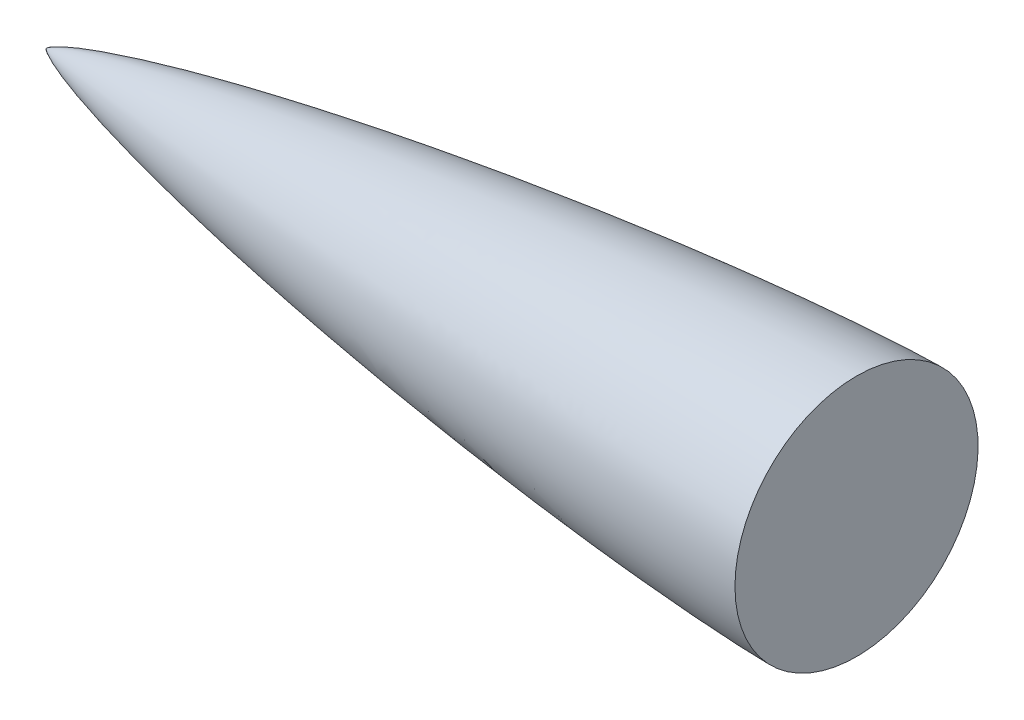
SolidWorks part; units mm, degrees
ref_plane "Front Plane" through (0, 0, 0) normal (0, 0, 1) x (1, 0, 0)
ref_plane "Top Plane" through (0, 0, 0) normal (0, 1, 0) x (1, 0, 0)
ref_plane "Right Plane" through (0, 0, 0) normal (1, 0, 0) x (0, 0, -1)
sketch "Sketch8" plane through (0, 0, 0) normal (0, 0, 1) x (1, 0, 0)
  line L0 (0, 0) -> (20, 0)
  line L1 (20, 0) -> (20, 3)
  spline S0 degree 4 poles (0, 0) (0.0015, 0.0033) (0.0052, 0.0087) (0.0122, 0.0154) (0.0228, 0.0245) (0.0364, 0.0347) (0.0573, 0.0488) (0.0927, 0.07) (0.1548, 0.1029) (0.2682, 0.1555) (0.4717, 0.2373) (0.8108, 0.355) (1.4143, 0.5368) (2.2722, 0.7584) (3.3422, 1.0012) (4.5729, 1.25) (5.8196, 1.4792) (7.3821, 1.7429) (8.9489, 1.9804) (10.5189, 2.1951) (12.0916, 2.388) (13.3514, 2.5294) (14.6126, 2.6574) (15.8751, 2.7712) (17.139, 2.8691) (18.3281, 2.9439) (19.2018, 2.983) (19.7593, 2.9983) (20, 3) knots 0 0 0 0 0 0.000709 0.001299 0.001888 0.002757 0.004048 0.006275 0.010003 0.016613 0.028658 0.049486 0.080709 0.140768 0.203215 0.265661 0.328107 0.390553 0.515445 0.577892 0.640338 0.702784 0.76523 0.827676 0.890122 0.952569 1 1 1 1 1 construction
  spline S1 degree 4 poles (0, 0) (0.0015, 0.0033) (0.0052, 0.0087) (0.0122, 0.0154) (0.0228, 0.0245) (0.0364, 0.0347) (0.0573, 0.0488) (0.0927, 0.07) (0.1548, 0.1029) (0.2682, 0.1555) (0.4717, 0.2373) (0.8108, 0.355) (1.4143, 0.5368) (2.2722, 0.7584) (3.3422, 1.0012) (4.5729, 1.25) (5.8196, 1.4792) (7.3821, 1.7429) (8.9489, 1.9804) (10.5189, 2.1951) (12.0916, 2.388) (13.3514, 2.5294) (14.6126, 2.6574) (15.8751, 2.7712) (17.139, 2.8691) (18.3281, 2.9439) (19.2018, 2.983) (19.7593, 2.9983) (20, 3) knots 0 0 0 0 0 0.000709 0.001299 0.001888 0.002757 0.004048 0.006275 0.010003 0.016613 0.028658 0.049486 0.080709 0.140768 0.203215 0.265661 0.328107 0.390553 0.515445 0.577892 0.640338 0.702784 0.76523 0.827676 0.890122 0.952569 1 1 1 1 1
  dimension "D1" = 20
revolve "Revolve8" add sketch "Sketch8" angle 360 about L0
